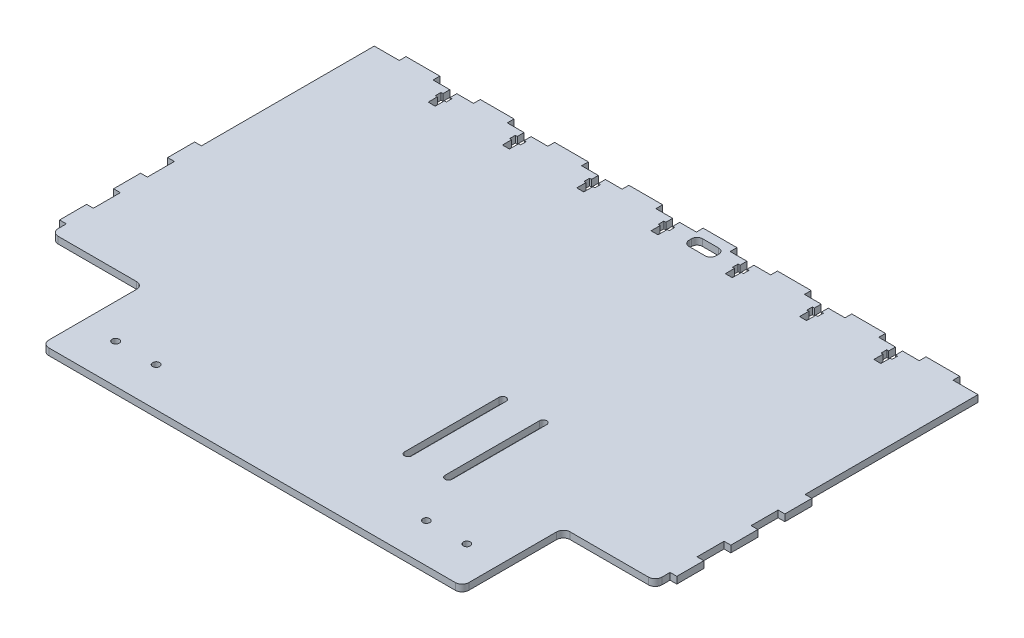
SolidWorks part; units mm, degrees
material "Acrílico (médio-alto impacto)"
ref_plane "Plano frontal" through (0, 0, 0) normal (0, 0, 1) x (1, 0, 0)
ref_plane "Plano superior" through (0, 0, 0) normal (0, 1, 0) x (1, 0, 0)
ref_plane "Plano direito" through (0, 0, 0) normal (1, 0, 0) x (0, 0, -1)
sketch "Esboço1" plane through (0, 0, 0) normal (0, 1, 0) x (1, 0, 0)
  line L1 (-223.5, 157) -> (223.5, 157)
  line L2 (-223.5, 157) -> (-223.5, -157)
  line L3 (-223.5, -157) -> (223.5, -157)
  line L4 (223.5, 157) -> (223.5, -157)
  line L5 (-223.5, 157) -> (223.5, -157) construction
  line L6 (-223.5, -157) -> (223.5, 157) construction
  point P0 (0, 0)
  dimension "D1" = 447
  dimension "D2" = 314
extrude "Ressalto-extrusão1" add sketch "Esboço1" along normal mid plane 5
sketch "Esboço2" plane through (0, 0, -157) normal (0, 0, -1) x (-1, 0, 0)
  line L0 (-223.5, 0) -> (223.5, 0) construction
  line L1 (-223.5, 2.5) -> (-223.5, -2.5) construction
  line L2 (223.5, 2.5) -> (223.5, -2.5) construction
  line L3 (-223.5, -2.5) -> (223.5, -2.5) construction
  line L4 (-205, 2.5) -> (-180, 2.5)
  line L5 (-205, 2.5) -> (-205, -2.5)
  line L6 (-205, -2.5) -> (-180, -2.5)
  line L7 (-180, 2.5) -> (-180, -2.5)
  line L8 (-205, 2.5) -> (-180, -2.5) construction
  line L9 (-205, -2.5) -> (-180, 2.5) construction
  point P6 (-192.5, 0)
  dimension "D1" = 25
  dimension "D2" = 18.5
extrude "Ressalto-extrusão2" add sketch "Esboço2" along normal blind 5
pattern_linear "Padrão linear1" count 8 spacing 55 along (-1, 0, 0) of "Ressalto-extrusão2"
sketch "Esboço3" plane through (0, 2.5, 0) normal (0, 1, 0) x (1, 0, 0)
  line L0 (223.5, 157) -> (205, 157) construction
  line L1 (167.6, 157) -> (162.4, 157)
  line L2 (167.6, 157) -> (167.6, 152)
  line L3 (167.6, 152) -> (162.4, 152)
  line L4 (162.4, 157) -> (162.4, 152)
  line L5 (223.5, -157) -> (223.5, 157) construction
  line L6 (169.05, 147.8) -> (160.95, 147.8)
  line L7 (169.05, 147.8) -> (169.05, 152)
  line L8 (169.05, 152) -> (160.95, 152)
  line L9 (160.95, 147.8) -> (160.95, 152)
  line L10 (167.6, 141) -> (162.4, 141)
  line L11 (167.6, 141) -> (167.6, 147.8)
  line L12 (167.6, 147.8) -> (162.4, 147.8)
  line L13 (162.4, 141) -> (162.4, 147.8)
  point P10 (165, 152)
  point P15 (165, 147.8)
  line M9 (223.5, 157) -> (205, 157)
  dimension "D1" = 5.2
  dimension "D2" = 4.2
  dimension "D3" = 8.1
  dimension "D4" = 5
  dimension "D5" = 5.2
  dimension "D6" = 16
  dimension "D7" = 58.5
extrude "Corte-extrusão1" cut sketch "Esboço3" against normal through all contours L13 L10 L11 L6 | L9 L6 L7 L8 L3 | L4 L3 L2 M9
pattern_linear "Padrão linear2" count 7 spacing 55 along (-1, 0, 0) of "Corte-extrusão1"
sketch "Esboço7" plane through (0, 2.5, 0) normal (0, 1, 0) x (1, 0, 0)
  line L1 (223.5, -157) -> (155.5, -157)
  line L2 (223.5, -157) -> (223.5, -82)
  line L3 (223.5, -82) -> (155.5, -82)
  line L4 (155.5, -157) -> (155.5, -82)
  dimension "D1" = 75
  dimension "D2" = 68
extrude "Corte-extrusão2" cut sketch "Esboço7" against normal blind 10
sketch "Esboço8" plane through (0, 2.5, 0) normal (0, 1, 0) x (1, 0, 0)
  line L0 (180, 157) -> (167.6, 157) construction
  circle A0 centre (130, -128) radius 2.6
  circle A1 centre (100, -128) radius 2.6
  point P9 (173.8, 157)
  dimension "D1" = 5.2
  dimension "D2" = 5.2
  dimension "D3" = 30
  dimension "D4" = 285
  dimension "D5" = 100
extrude "Corte-extrusão3" cut sketch "Esboço8" against normal through all
mirror "Espelhar2" about plane through (0, 0, 0) normal (1, 0, 0) of "Corte-extrusão3", "Corte-extrusão2"
fillet "Filete1" radius 5 6 edges at (223.5, 0, 82) (155.5, 0, 157) (155.5, 0, 82) (-155.5, 0, 82) (-223.5, 0, 82) (-155.5, 0, 157)
sketch "Esboço9" plane through (223.5, 0, 0) normal (1, 0, 0) x (0, 0, -1)
  line L0 (-77, -2.5) -> (157, -2.5) construction
  line L1 (-71, 2.5) -> (-51, 2.5)
  line L2 (-71, 2.5) -> (-71, -2.5)
  line L3 (-71, -2.5) -> (-51, -2.5)
  line L4 (-51, 2.5) -> (-51, -2.5)
  line L5 (-71, 2.5) -> (-51, -2.5) construction
  line L6 (-71, -2.5) -> (-51, 2.5) construction
  line L8 (-82, -2.5) -> (-82, 2.5) construction
  line L9 (-77, 2.5) -> (157, 2.5) construction
  point P0 (-61, 0)
  dimension "D1" = 20
  dimension "D2" = 11
extrude "Ressalto-extrusão3" add sketch "Esboço9" along normal blind 5
pattern_linear "Padrão linear3" count 3 spacing 40 along (0, 0, -1) of "Ressalto-extrusão3"
mirror "Espelhar3" about plane through (0, 0, 0) normal (1, 0, 0) of "Padrão linear3", "Ressalto-extrusão3"
sketch "Esboço10" plane through (0, 2.5, 0) normal (0, 1, 0) x (1, 0, 0)
  line L0 (223.5, 29) -> (223.5, 157) construction
  line L1 (215.5, 1.75) -> (118.98, 1.75)
  line L2 (215.5, 1.75) -> (215.5, 97)
  line L3 (215.5, 97) -> (118.98, 97)
  line L4 (118.98, 1.75) -> (118.98, 97)
  line L5 (215.5, 1.75) -> (118.98, 97) construction
  line L6 (215.5, 97) -> (118.98, 1.75) construction
  line L7 (107.4, 157) -> (95, 157) construction
  circle A0 centre (215.5, 1.75) radius 1.75
  circle A1 centre (118.98, 1.75) radius 1.75
  circle A2 centre (215.5, 97) radius 1.75
  circle A3 centre (118.98, 97) radius 1.75
  point P0 (167.24, 49.375)
  point P13 (101.2, 157)
  dimension "D3" = 3.5
  dimension "D4" = 3.5
  dimension "D5" = 3.5
  dimension "D6" = 3.5
  dimension "D1" = 96.52
  dimension "D2" = 95.25
  dimension "D7" = 8
  dimension "D8" = 60
extrude "Corte-extrusão4" [suppressed] cut sketch "Esboço10" against normal through all contours A0 | A1 | A2 | A3
sketch "Esboço11" plane through (0, 2.5, 0) normal (0, 1, 0) x (1, 0, 0)
  line L0 (-223.5, -31) -> (-223.5, -51) construction
  line L1 (-28.5, -48) -> (-113.5, -48)
  line L2 (-28.5, -48) -> (-28.5, 77)
  line L3 (-28.5, 77) -> (-113.5, 77)
  line L4 (-113.5, -48) -> (-113.5, 77)
  line L5 (-28.5, -48) -> (-113.5, 77) construction
  line L6 (-28.5, 77) -> (-113.5, -48) construction
  line L7 (-112.6, 157) -> (-125, 157) construction
  circle A0 centre (-28.5, 77) radius 1.75
  circle A1 centre (-113.5, 77) radius 1.75
  circle A2 centre (-28.5, -48) radius 1.75
  circle A3 centre (-113.5, -48) radius 1.75
  point P0 (-71, 14.5)
  point P11 (-223.5, -41)
  dimension "D3" = 3.5
  dimension "D4" = 3.5
  dimension "D5" = 3.5
  dimension "D6" = 3.5
  dimension "D1" = 85
  dimension "D2" = 125
  dimension "D7" = 110
  dimension "D8" = 80
extrude "Corte-extrusão5" [suppressed] cut sketch "Esboço11" against normal blind 10 contours A2 | A3 | A1 | A0
sketch "Esboço12" plane through (0, 2.5, 0) normal (0, 1, 0) x (1, 0, 0)
  line L0 (65.5, -157) -> (65.5, 157) construction
  line L4 (-150.5, -157) -> (150.5, -157) construction
  line L5 (125, 157) -> (112.6, 157) construction
  line L6 (155.5, -87) -> (155.5, -152) construction
  line L7 (223.5, -57) -> (-223.5, -57) construction
  line L8 (223.5, -11) -> (223.5, 9) construction
  line L9 (-223.5, 9) -> (-223.5, -11) construction
  line L10 (50.5, -22) -> (50.5, -92) construction
  line L11 (53.1, -22) -> (53.1, -92)
  line L12 (47.9, -22) -> (47.9, -92)
  line L13 (80.5, -22) -> (80.5, -92) construction
  line L14 (77.9, -22) -> (77.9, -92)
  line L15 (83.1, -22) -> (83.1, -92)
  arc A0 (53.1, -22) -> (47.9, -22) centre (50.5, -22) ccw
  arc A1 (47.9, -92) -> (53.1, -92) centre (50.5, -92) ccw
  arc A2 (77.9, -22) -> (83.1, -22) centre (80.5, -22) cw
  arc A3 (83.1, -92) -> (77.9, -92) centre (80.5, -92) cw
  point P16 (50.5, -57)
  point P23 (80.5, -57)
  dimension "D1" = 90
  dimension "D2" = 100
  dimension "D3" = 5.2
  dimension "D4" = 70
  dimension "D5" = 15
extrude "Corte-extrusão6" cut sketch "Esboço12" against normal through all
sketch "Esboço13" plane through (0, -2.5, 0) normal (0, -1, 0) x (1, 0, 0)
  line L0 (223.5, 1) -> (-223.5, 1) construction
  line L1 (223.5, 11) -> (223.5, -9) construction
  line L2 (-223.5, -9) -> (-223.5, 11) construction
  line L3 (-155.5, 101) -> (155.5, 101) construction
  line L4 (-155.5, 87) -> (-155.5, 152) construction
  line L5 (155.5, 87) -> (155.5, 152) construction
  circle A0 centre (-140.5, 101) radius 1.75
  circle A1 centre (-120.5, 101) radius 1.75
  dimension "D1" = 100
  dimension "D2" = 3.5
  dimension "D4" = 3.5
  dimension "D3" = 15
  dimension "D5" = 20
extrude "Corte-extrusão7" [suppressed] cut sketch "Esboço13" against normal through all
sketch "Esboço17" plane through (0, 2.5, 0) normal (0, 1, 0) x (1, 0, 0)
  line L1 (40, 162) -> (40, 157) construction
  line L2 (37.5, 155) -> (17.5, 155)
  line L3 (37.5, 155) -> (37.5, 145)
  line L4 (37.5, 145) -> (17.5, 145)
  line L6 (17.5, 155) -> (17.5, 145)
  line L8 (15, 157) -> (2.6, 157) construction
  dimension "D1" = 2.5
  dimension "D2" = 20
  dimension "D3" = 10
  dimension "D4" = 2
extrude "Corte-extrusão10" cut sketch "Esboço17" against normal through all
fillet "Filete2" radius 4 4 edges at (17.5, 0, -155) (17.5, 0, -145) (37.5, 0, -155) (37.5, 0, -145)
